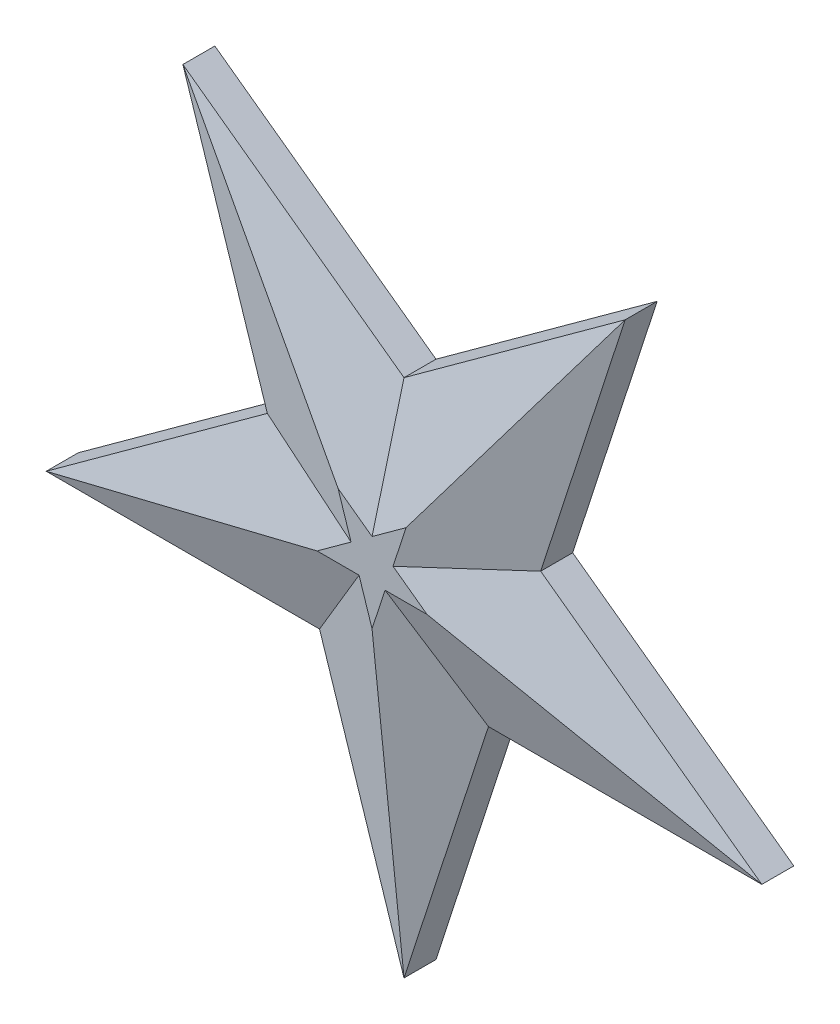
SolidWorks part; units mm, degrees
ref_plane "Alzado" through (0, 0, 0) normal (0, 0, 1) x (1, 0, 0)
ref_plane "Planta" through (0, 0, 0) normal (0, 1, 0) x (1, 0, 0)
ref_plane "Vista lateral" through (0, 0, 0) normal (1, 0, 0) x (0, 0, -1)
sketch "Croquis1" plane through (0, 0, 0) normal (0, 0, 1) x (1, 0, 0)
  line L0 (-32.321, -11.7021) -> (19.6204, -11.7021) construction
  line L2 (-6.3503, -35.2367) -> (16.0325, -18.9747) construction
  line L3 (16.0325, -18.9747) -> (7.483, 7.3378) construction
  line L4 (7.483, 7.3378) -> (-20.1836, 7.3378) construction
  line L5 (-20.1836, 7.3378) -> (-28.733, -18.9747) construction
  line L6 (-28.733, -18.9747) -> (-6.3503, -35.2367) construction
  line L8 (-6.3503, -35.2367) -> (-11.6341, -18.9747)
  line L14 (-20.1836, 7.3378) -> (-6.3503, -2.7126)
  line L15 (16.0325, -18.9747) -> (-1.0664, -18.9747)
  line L16 (-28.733, -18.9747) -> (-14.8997, -8.9242)
  line L17 (7.483, 7.3378) -> (2.1992, -8.9242)
  line L23 (-11.6341, -18.9747) -> (-28.733, -18.9747)
  line L24 (-14.8997, -8.9242) -> (-20.1836, 7.3378)
  line L25 (-6.3503, -2.7126) -> (7.483, 7.3378)
  line L26 (2.1992, -8.9242) -> (16.0325, -18.9747)
  line L27 (-1.0664, -18.9747) -> (-6.3503, -35.2367)
  circle A0 centre (-6.3503, -11.7021) radius 19.0399 construction
  dimension "D1" = 11.7021
  dimension "D3" = 27.6666
  dimension "D4" = 6.3503
extrude "Saliente-Extruir1" add sketch "Croquis1" along normal blind 2
sketch "Croquis2" plane through (0, 0, 2) normal (0, 0, 1) x (1, 0, 0)
  line L0 (-32.321, -11.7021) -> (19.6204, -11.7021) construction
  line L1 (-6.3503, -11.7021) -> (-28.733, -18.9747)
  line L2 (-14.8997, -8.9242) -> (-28.733, -18.9747) construction
  line L3 (-6.3503, -11.7021) -> (-20.1836, 7.3378)
  line L4 (-20.1836, 7.3378) -> (-14.8997, -8.9242) construction
  line L5 (-6.3503, -2.7126) -> (-20.1836, 7.3378) construction
  line L6 (7.483, 7.3378) -> (-6.3503, -11.7021)
  line L7 (2.1992, -8.9242) -> (7.483, 7.3378) construction
  line L8 (-6.3503, -35.2367) -> (-6.3503, -11.7021)
  line L9 (-6.3503, -35.2367) -> (-1.0664, -18.9747) construction
  line L10 (16.0325, -18.9747) -> (-6.3503, -11.7021)
  line L11 (-1.0664, -18.9747) -> (16.0325, -18.9747) construction
  line M2 (-6.3503, -35.2367) -> (-1.0664, -18.9747)
  line M3 (-1.0664, -18.9747) -> (16.0325, -18.9747)
  line M4 (16.0325, -18.9747) -> (2.1992, -8.9242)
  line M5 (2.1992, -8.9242) -> (7.483, 7.3378)
  line M6 (7.483, 7.3378) -> (-6.3503, -2.7126)
  line M7 (-6.3503, -2.7126) -> (-20.1836, 7.3378)
  line M8 (-20.1836, 7.3378) -> (-14.8997, -8.9242)
  line M9 (-14.8997, -8.9242) -> (-28.733, -18.9747)
  line M10 (-28.733, -18.9747) -> (-11.6341, -18.9747)
  line M11 (-11.6341, -18.9747) -> (-6.3503, -35.2367)
extrude "Saliente-Extruir2" add sketch "Croquis2" along normal blind 2 draft 72 contours L10 L8 M3 M2 | L8 L1 M11 M10 | L6 L0 M4 M5 | L6 L3 M6 M7 | L0 L3 M9 M8 | L0 L1 M9 | L0 L10 M4
